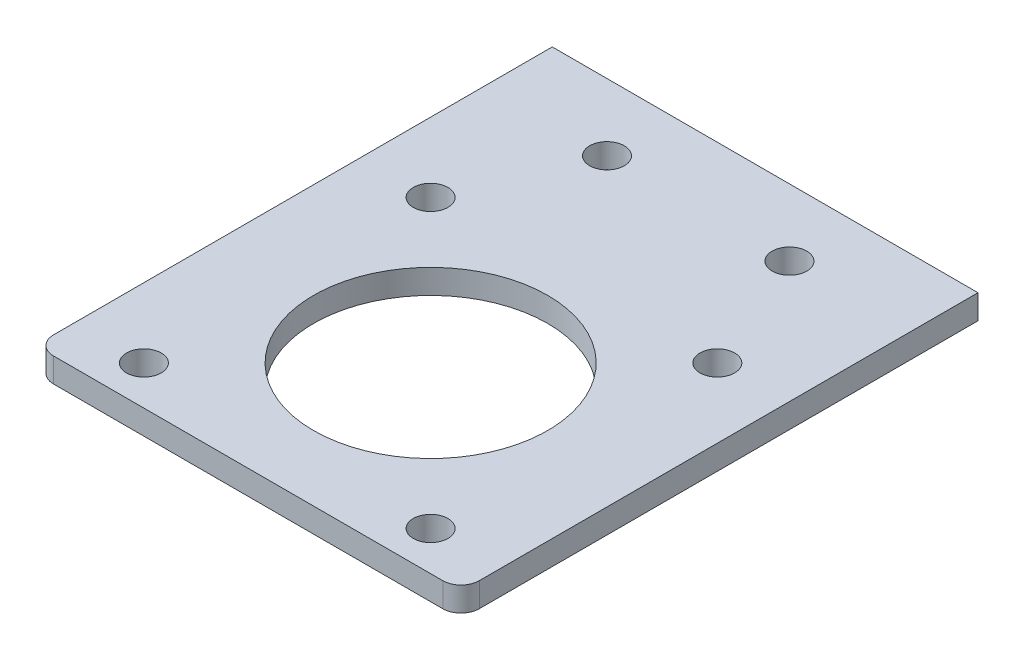
SolidWorks part; units mm, degrees
ref_plane "Front Plane" through (0, 0, 0) normal (0, 0, 1) x (1, 0, 0)
ref_plane "Top Plane" through (0, 0, 0) normal (0, 1, 0) x (1, 0, 0)
ref_plane "Right Plane" through (0, 0, 0) normal (1, 0, 0) x (0, 0, -1)
sketch "Sketch1" plane through (0, 0, 0) normal (0, 1, 0) x (1, 0, 0)
  line L1 (35, -42.5) -> (-35, -42.5)
  line L2 (35, -42.5) -> (35, 42.5)
  line L3 (35, 42.5) -> (-35, 42.5)
  line L4 (-35, -42.5) -> (-35, 42.5)
  line L5 (35, -42.5) -> (-35, 42.5) construction
  line L6 (35, 42.5) -> (-35, -42.5) construction
  point P0 (0, 0)
  dimension "D1" = 70
  dimension "D2" = 85
extrude "Boss-Extrude1" add sketch "Sketch1" along normal blind 4
sketch "Sketch2" plane through (0, 4, 0) normal (0, 1, 0) x (1, 0, 0)
  line L0 (0, -12.5) -> (0, -32.5759) construction
  line L1 (0, -12.5) -> (22.2974, -12.5) construction
  line L2 (0, -30.2326) -> (0, 30.2326) construction
  line L3 (35, 42.5) -> (-35, 42.5) construction
  circle A0 centre (-23.57, 11.07) radius 2.85
  circle A1 centre (-23.57, -36.07) radius 2.85
  circle A2 centre (23.57, -36.07) radius 2.85
  circle A3 centre (23.57, 11.07) radius 2.85
  circle A4 centre (0, -12.5) radius 19.25
  circle A5 centre (15, 31.5) radius 2.85
  circle A6 centre (-15, 31.5) radius 2.85
  dimension "D3" = 5.7
  dimension "D6" = 5.7
  dimension "D7" = 15
  dimension "D8" = 38.5
  dimension "D1" = 47.14
  dimension "D2" = 47.14
  dimension "D4" = 55
  dimension "D5" = 11
extrude "Cut-Extrude1" cut sketch "Sketch2" against normal through all
fillet "Fillet1" radius 3 2 edges at (35, 2, 42.5) (-35, 2, 42.5)
